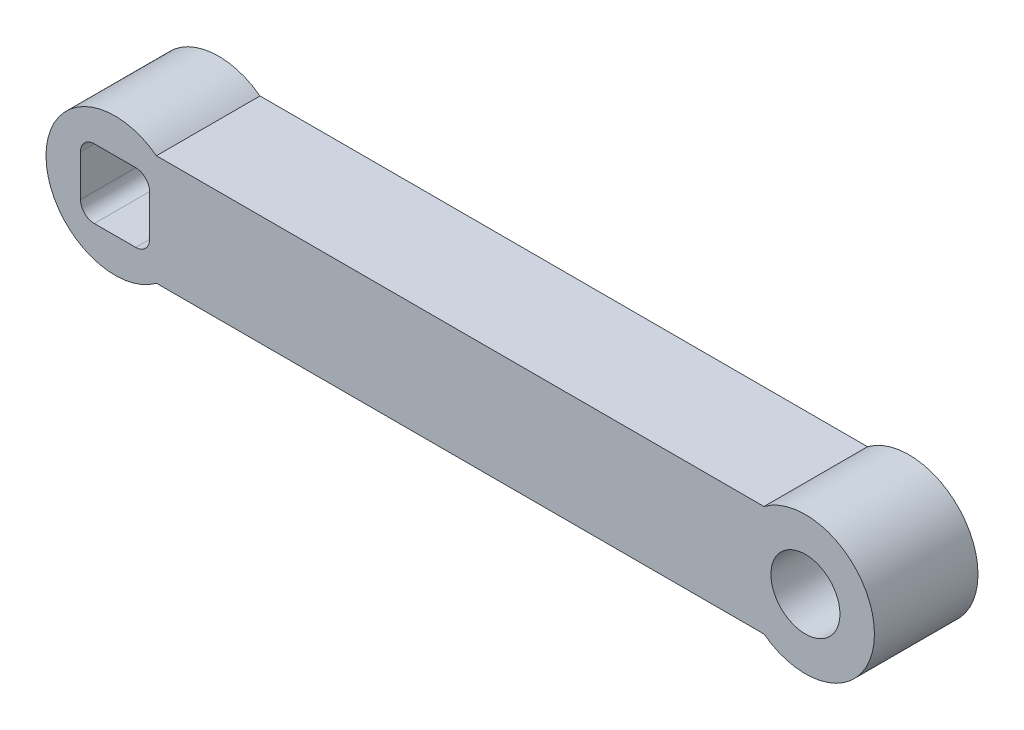
SolidWorks part; units mm, degrees
ref_plane "Front Plane" through (0, 0, 0) normal (0, 0, 1) x (1, 0, 0)
ref_plane "Top Plane" through (0, 0, 0) normal (0, 1, 0) x (1, 0, 0)
ref_plane "Right Plane" through (0, 0, 0) normal (1, 0, 0) x (0, 0, -1)
sketch "Sketch1" plane through (0, 0, 0) normal (0, 0, 1) x (1, 0, 0)
  line L0 (0, 0) -> (-50, 0) construction
  line L1 (-50, 0) -> (-50, 4) construction
  line L2 (-51.5, -2.5) -> (-48.5, -2.5)
  line L3 (-52.5, -1.5) -> (-52.5, 1.5)
  line L4 (-51.5, 2.5) -> (-48.5, 2.5)
  line L5 (-47.5, -1.5) -> (-47.5, 1.5)
  line L6 (-52.5, -2.5) -> (-47.5, 2.5) construction
  line L7 (-52.5, 2.5) -> (-47.5, -2.5) construction
  line L8 (-47, 4) -> (-3, 4)
  line L9 (-47, -4) -> (-3, -4)
  circle A0 centre (0, 0) radius 2.5
  arc A1 (-3, -4) -> (-3, 4) centre (0, 0) ccw
  arc A2 (-47, 4) -> (-47, -4) centre (-50, 0) ccw
  arc A3 (-48.5, -2.5) -> (-47.5, -1.5) centre (-48.5, -1.5) ccw
  arc A4 (-48.5, 2.5) -> (-47.5, 1.5) centre (-48.5, 1.5) cw
  arc A5 (-51.5, -2.5) -> (-52.5, -1.5) centre (-51.5, -1.5) cw
  arc A6 (-52.5, 1.5) -> (-51.5, 2.5) centre (-51.5, 1.5) cw
  dimension "D1" = 5
  dimension "D2" = 10
  dimension "D6" = 10
  dimension "D8" = 1
  dimension "D3" = 50
  dimension "D4" = 5
  dimension "D5" = 5
  dimension "D7" = 4
extrude "Boss-Extrude1" add sketch "Sketch1" along normal blind 7.5
